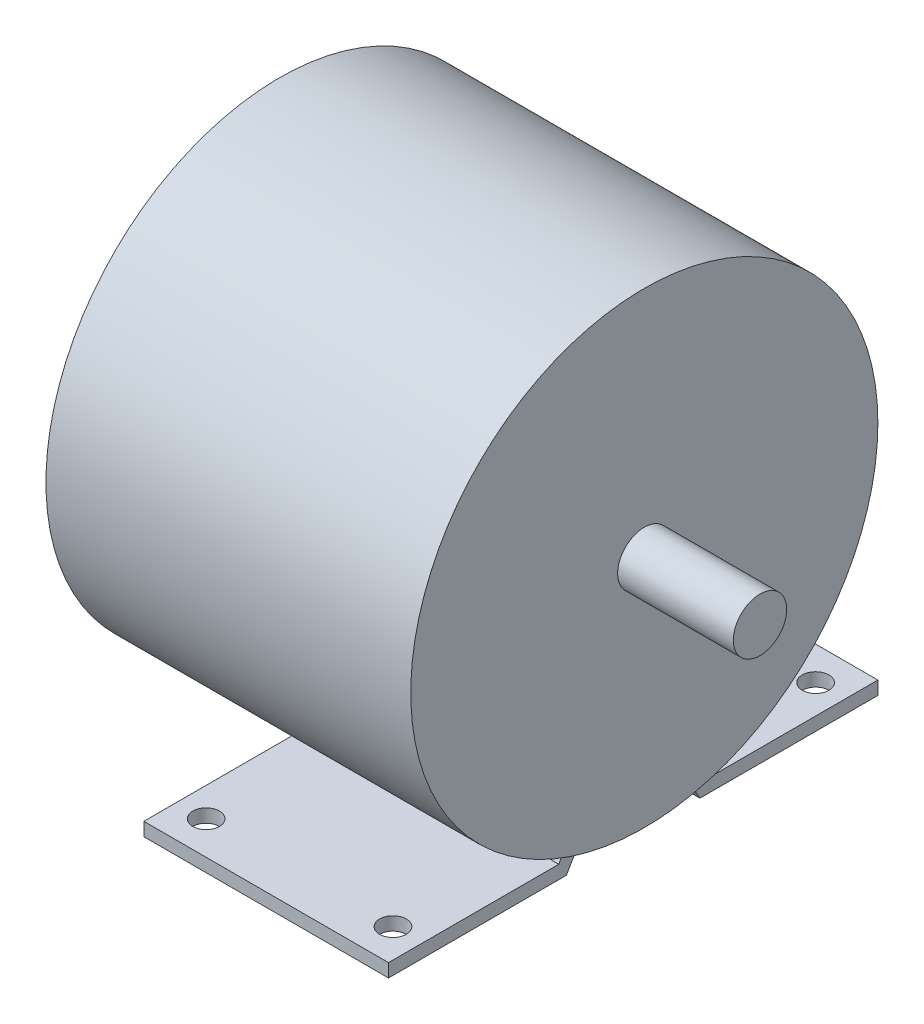
SolidWorks part; units mm, degrees
material "Custom Plastic"
ref_plane "Front Plane" through (0, 0, 0) normal (0, 0, 1) x (1, 0, 0)
ref_plane "Top Plane" through (0, 0, 0) normal (0, 1, 0) x (1, 0, 0)
ref_plane "Right Plane" through (0, 0, 0) normal (1, 0, 0) x (0, 0, -1)
sketch "Sketch1" plane through (0, 0, 0) normal (1, 0, 0) x (0, 0, -1)
  circle A0 centre (0, 0) radius 52.5
  dimension "D1" = 105
extrude "Boss-Extrude1" add sketch "Sketch1" along normal blind 82
sketch "Sketch2" plane through (82, 0, 0) normal (1, 0, 0) x (0, 0, -1)
  circle A0 centre (0, 0) radius 6
  dimension "D1" = 12
extrude "Boss-Extrude2" add sketch "Sketch2" along normal blind 26
ref_plane "Plane1" through (79.5, 0, 0) normal (1, 0, 0) x (0, 0, -1)
sketch "Sketch3" plane through (79.5, 0, 0) normal (1, 0, 0) x (0, 0, -1)
  line L0 (-55, -52.5) -> (-16.7321, -52.5)
  line L1 (-15, -55.5) -> (-12.4091, -51.0124)
  line L2 (-55, -52.5) -> (-55, -55.5)
  line L3 (-55, -55.5) -> (-15, -55.5)
  line L4 (-16.7321, -52.5) -> (-15.3989, -50.1909)
  line L5 (0, 0) -> (0, -52.5) construction
  line L6 (16.7321, -52.5) -> (15.3989, -50.1909)
  line L7 (55, -55.5) -> (15, -55.5)
  line L8 (55, -52.5) -> (55, -55.5)
  line L9 (15, -55.5) -> (12.4091, -51.0124)
  line L10 (55, -52.5) -> (16.7321, -52.5)
  circle A1 centre (0, 0) radius 52.5 construction
  arc A2 (-15.3989, -50.1909) -> (-12.4091, -51.0124) centre (0, 0) ccw
  arc A3 (15.3989, -50.1909) -> (12.4091, -51.0124) centre (0, 0) cw
  dimension "D1" = 3
  dimension "D2" = 40
  dimension "D3" = 3
  dimension "D4" = 55
  dimension "D5" = 60
extrude "Boss-Extrude3" add sketch "Sketch3" against normal blind 55
sketch "Sketch4" plane through (0, -55.5, 0) normal (0, -1, 0) x (1, 0, 0)
  line L0 (103.9578, 0) -> (49.9114, 0) construction
  line L1 (79.5, 55) -> (79.5, 15) construction
  circle A0 centre (73, 47.5) radius 3
  circle A1 centre (73, -47.5) radius 3
  circle A2 centre (31, -47.5) radius 3
  circle A3 centre (31, 47.5) radius 3
  dimension "D2" = 6
  dimension "D1" = 47.5
  dimension "D4" = 42
  dimension "D5" = 6.5
  dimension "D3" = 2
extrude "Cut-Extrude1" cut sketch "Sketch4" against normal up to next
